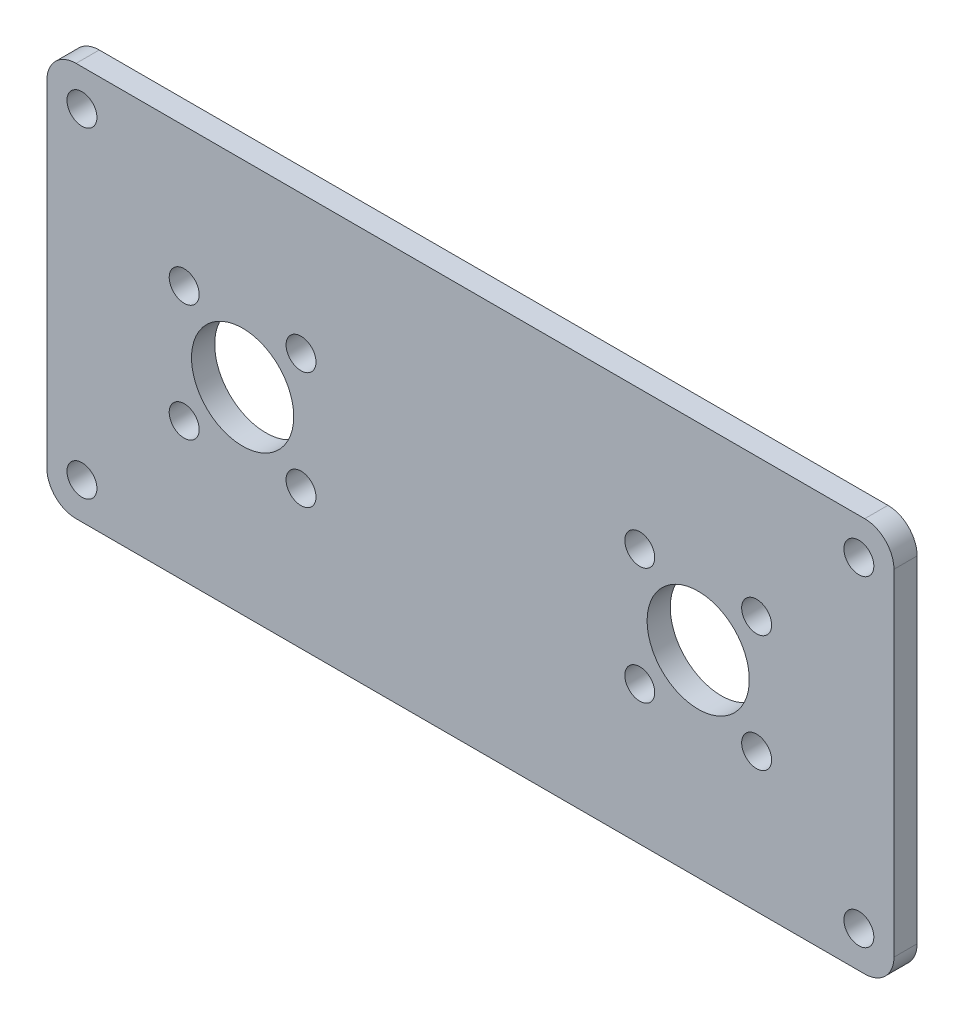
SolidWorks part; units mm, degrees
ref_plane "Front Plane" through (0, 0, 0) normal (0, 0, 1) x (1, 0, 0)
ref_plane "Top Plane" through (0, 0, 0) normal (0, 1, 0) x (1, 0, 0)
ref_plane "Right Plane" through (0, 0, 0) normal (1, 0, 0) x (0, 0, -1)
sketch "Sketch1" plane through (0, 0, 0) normal (0, 0, 1) x (1, 0, 0)
  line L0 (5.7141, 0) -> (-49994.2859, 0) construction
  line L1 (58, -27) -> (-58, -27)
  line L2 (58, -27) -> (58, 27)
  line L3 (58, 27) -> (-58, 27)
  line L4 (-58, -27) -> (-58, 27)
  line L5 (58, -27) -> (-58, 27) construction
  line L6 (58, 27) -> (-58, -27) construction
  line L7 (53.195, 22) -> (-53.195, 22) construction
  line L8 (53.195, 22) -> (53.195, -22) construction
  line L9 (53.195, -22) -> (-53.195, -22) construction
  line L10 (-53.195, 22) -> (-53.195, -22) construction
  line L11 (53.195, 22) -> (-53.195, -22) construction
  line L12 (53.195, -22) -> (-53.195, 22) construction
  line L13 (0, 0) -> (0, -50000) construction
  line L14 (-39.195, 8) -> (-23.195, 8) construction
  line L15 (-39.195, 8) -> (-39.195, -8) construction
  line L16 (-39.195, -8) -> (-23.195, -8) construction
  line L17 (-23.195, 8) -> (-23.195, -8) construction
  line L18 (-39.195, 8) -> (-23.195, -8) construction
  line L19 (-39.195, -8) -> (-23.195, 8) construction
  circle A0 centre (-53.195, 22) radius 2.05
  circle A1 centre (53.195, 22) radius 2.05
  circle A2 centre (53.195, -22) radius 2.05
  circle A3 centre (-53.195, -22) radius 2.05
  circle A4 centre (-39.195, 8) radius 2.05
  circle A5 centre (-23.195, 8) radius 2.05
  circle A6 centre (-23.195, -8) radius 2.05
  circle A7 centre (-39.195, -8) radius 2.05
  circle A8 centre (-31.195, 0) radius 7
  circle A9 centre (39.195, -8) radius 2.05
  circle A10 centre (39.195, 8) radius 2.05
  circle A11 centre (23.195, 8) radius 2.05
  circle A12 centre (31.195, 0) radius 7
  circle A13 centre (23.195, -8) radius 2.05
  point P0 (0, 0)
  point P6 (0, 0)
  point P17 (-31.195, 0)
  dimension "D5" = 4.1
  dimension "D9" = 14
  dimension "D1" = 116
  dimension "D2" = 54
  dimension "D3" = 106.39
  dimension "D4" = 44
  dimension "D6" = 16
  dimension "D7" = 16
  dimension "D8" = 22
extrude "Boss-Extrude1" add sketch "Sketch1" along normal blind 3.175
fillet "Fillet1" radius 4 4 edges at (-58, -27, 1.5875) (58, -27, 1.5875) (58, 27, 1.5875) (-58, 27, 1.5875)
